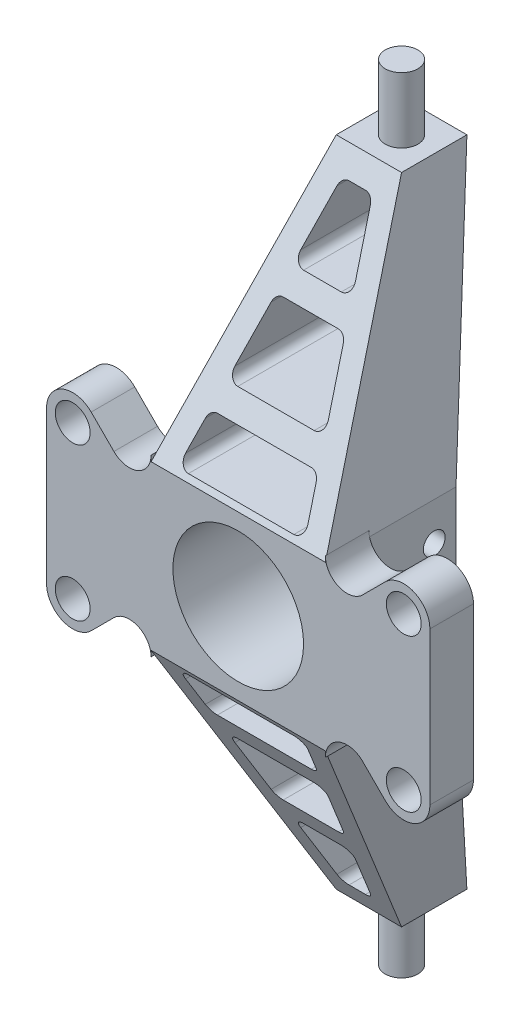
SolidWorks part; units mm, degrees
material "Cast Alloy Steel"
ref_plane "Front Plane" through (0, 0, 0) normal (0, 0, 1) x (1, 0, 0)
ref_plane "Top Plane" through (0, 0, 0) normal (0, 1, 0) x (1, 0, 0)
ref_plane "Right Plane" through (0, 0, 0) normal (1, 0, 0) x (0, 0, -1)
sketch "Sketch1" plane through (0, 0, 0) normal (1, 0, 0) x (0, 0, -1)
  line L1 (-15, -18.75) -> (-15, 18.75)
  line L2 (-15, 18.75) -> (15, 75)
  line L3 (15, 75) -> (30, 75)
  line L4 (30, 75) -> (15, 18.75)
  line L5 (15, 18.75) -> (15, -18.75)
  line L6 (-59.1587, 0) -> (-15, 0) construction
  line L7 (30, -75) -> (15, -18.75)
  line L8 (15, -75) -> (30, -75)
  line L9 (-15, -18.75) -> (15, -75)
  line L10 (15, 0) -> (64.9977, 0) construction
  line L11 (-15, 0) -> (0, 0) construction
  line L12 (0, 0) -> (15, 0) construction
  point P8 (15, 18.8912)
  dimension "D2" = 30
  dimension "D4" = 30
  dimension "D5" = 15
  dimension "D3" = 150
  dimension "D1" = 37.5
extrude "Boss-Extrude1" add sketch "Sketch1" along normal mid plane 40
sketch "Sketch2" plane through (0, 0, 15) normal (0, 0, 1) x (1, 0, 0)
  circle A0 centre (0, 0) radius 15
  dimension "D1" = 30
extrude "Cut-Extrude1" cut sketch "Sketch2" against normal through all both and the other way through all
sketch "Sketch3" plane through (0, 0, 15) normal (0, 0, 1) x (1, 0, 0)
  line L0 (-28.5355, 16.5208) -> (-33.7574, 21.7426)
  line L1 (-20, -18.75) -> (-20, 18.75) construction
  line L2 (-44, 17.5) -> (-44, -17.5)
  line L3 (-33.7574, -21.7426) -> (-28.5355, -16.5208)
  line L4 (-20, -18.75) -> (-20, -20.0563)
  line L5 (-20, 20.0563) -> (-20, 18.75)
  line L6 (-44, 0) -> (13.7226, 0) construction
  arc A0 (-20, -20.0563) -> (-28.5355, -16.5208) centre (-25, -20.0563) ccw
  arc A1 (-20, 20.0563) -> (-28.5355, 16.5208) centre (-25, 20.0563) cw
  arc A2 (-33.7574, -21.7426) -> (-44, -17.5) centre (-38, -17.5) cw
  arc A3 (-44, 17.5) -> (-33.7574, 21.7426) centre (-38, 17.5) cw
  circle A4 centre (-38, 17.5) radius 4
  circle A5 centre (-38, -17.5) radius 4
  arc A6 (-44, -17.5) -> (-33.7574, -21.7426) centre (-38, -17.5) ccw
  circle A7 centre (-38, -17.5) radius 6 construction
  point P8 (-20, -7.9853)
  point P11 (-20, 7.9853)
  point P18 (-44, 0)
  point P24 (0, 0)
  line M8 (-20, 18.75) -> (-20, -18.75)
  dimension "D1" = 5
  dimension "D2" = 2
  dimension "D4" = 8
  dimension "D3" = 35
  dimension "D5" = 18
  dimension "D6" = 45
extrude "Boss-Extrude2" add sketch "Sketch3" against normal blind 10 separate body contours A3 L2 A2 L3 A0 A1 L0 A5 A4 M8
sketch "Sketch5" plane through (0, 75, 0) normal (0, 1, 0) x (1, 0, 0)
  line L0 (0, 22.5) -> (0, 30) construction
  line L1 (20, 30) -> (-20, 30) construction
  line L2 (0, 22.5) -> (20, 22.5) construction
  line L3 (20, 15) -> (20, 30) construction
  circle A0 centre (0, 22.5) radius 3.75
  dimension "D1" = 7.5
extrude "Boss-Extrude3" add sketch "Sketch5" along normal blind 15
mirror "Mirror1" about plane through (0, 0, 0) normal (0, 1, 0) of "Boss-Extrude3"
sketch "Sketch6" plane through (0, 0, 15) normal (0, 0, 1) x (1, 0, 0)
  line L0 (-20, 18.75) -> (-7.5, 75)
  line L1 (20, 75) -> (-20, 75) construction
  line L2 (20, 18.75) -> (7.5, 75)
  line L4 (-20, 18.75) -> (-20, -18.75)
  line L5 (-20, -18.75) -> (20, -18.75)
  line L6 (20, -18.75) -> (20, 18.75)
  line L7 (20, 18.75) -> (-20, 18.75)
  line L10 (20, -18.75) -> (20, 18.75)
  line L12 (-7.5, 75) -> (-20, 75)
  line L16 (-20, 75) -> (-20, 18.75)
  line L17 (-20, 18.75) -> (20, 18.75)
  line L18 (20, 18.75) -> (20, 75)
  line L19 (20, 75) -> (-20, 75)
  line L20 (-20, 75) -> (-20, 18.75)
  line L22 (20, 18.75) -> (20, 75)
  line L23 (20, 75) -> (7.5, 75)
  dimension "D2" = 12.5
  dimension "D1" = 0
  dimension "D3" = 0
extrude "Cut-Extrude2" cut sketch "Sketch6" against normal through all both and the other way through all contours L22 L23 L2 | L20 L0 L12
mirror "Mirror2" about plane through (0, 0, 0) normal (0, 1, 0) of "Cut-Extrude2"
sketch "Sketch7" plane through (0, 0, 0) normal (0, 0, 1) x (1, 0, 0)
  line L0 (-12.107, 20) -> (12.107, 20)
  line L1 (14.0594, 22.4339) -> (12.7261, 28.4339)
  line L2 (1.8848, 70) -> (-1.8848, 70)
  line L3 (-3.8372, 68.4339) -> (-6.2816, 57.4339)
  line L4 (7.5, 75) -> (-7.5, 75) construction
  line L5 (-20, 18.75) -> (-7.5, 75) construction
  line L6 (20, 18.75) -> (7.5, 75) construction
  line L16 (-10.7737, 30) -> (10.7737, 30)
  line L17 (-8.7737, 35) -> (8.7737, 35)
  line L18 (-6.3292, 50) -> (6.3292, 50)
  line L19 (-4.3292, 55) -> (4.3292, 55)
  line L21 (-8.2816, 48.4339) -> (-10.7261, 37.4339)
  line L23 (6.2816, 57.4339) -> (3.8372, 68.4339)
  line L25 (-12.7261, 28.4339) -> (-14.0594, 22.4339)
  line L26 (10.7261, 37.4339) -> (8.2816, 48.4339)
  arc A0 (14.0594, 22.4339) -> (12.107, 20) centre (12.107, 22) cw
  arc A1 (12.7261, 28.4339) -> (10.7737, 30) centre (10.7737, 28) ccw
  arc A2 (-14.0594, 22.4339) -> (-12.107, 20) centre (-12.107, 22) ccw
  arc A3 (-12.7261, 28.4339) -> (-10.7737, 30) centre (-10.7737, 28) cw
  arc A4 (10.7261, 37.4339) -> (8.7737, 35) centre (8.7737, 37) cw
  arc A5 (-8.2816, 48.4339) -> (-6.3292, 50) centre (-6.3292, 48) cw
  arc A6 (8.2816, 48.4339) -> (6.3292, 50) centre (6.3292, 48) ccw
  arc A7 (-8.7737, 35) -> (-10.7261, 37.4339) centre (-8.7737, 37) cw
  arc A8 (6.2816, 57.4339) -> (4.3292, 55) centre (4.3292, 57) cw
  arc A9 (-6.2816, 57.4339) -> (-4.3292, 55) centre (-4.3292, 57) ccw
  arc A10 (3.8372, 68.4339) -> (1.8848, 70) centre (1.8848, 68) ccw
  arc A11 (-1.8848, 70) -> (-3.8372, 68.4339) centre (-1.8848, 68) ccw
  point P16 (0, 50)
  point P27 (-12.378, 30)
  point P30 (11.2669, 35)
  point P33 (-7.9336, 50)
  point P38 (-11.2669, 35)
  point P41 (6.8225, 55)
  dimension "D7" = 2
  dimension "D3" = 5
  dimension "D4" = 5
  dimension "D5" = 10
  dimension "D6" = 15
  dimension "D8" = 5
  dimension "D2" = 15
  dimension "D1" = 5
  dimension "D9" = 5
extrude "Cut-Extrude3" cut sketch "Sketch7" against normal through all both and the other way through all
mirror "Mirror3" about plane through (0, 0, 0) normal (0, 1, 0) of "Cut-Extrude3"
mirror "Mirror6" about plane through (0, 0, 0) normal (1, 0, 0) of "Boss-Extrude2"
combine bodies "Combine1" operation type add bodies to combine 110 103
sketch "Sketch8" plane through (20, 0, 0) normal (1, 0, 0) x (0, 0, -1)
  line L0 (15, 18.75) -> (-5, 18.75) construction
  line L1 (15, 18.75) -> (15, -18.75) construction
  line L2 (10, 10) -> (10, 18.75) construction
  line L3 (10, -10) -> (10, -18.75) construction
  line L4 (15, -18.75) -> (-5, -18.75) construction
  circle A0 centre (10, 10) radius 2.5
  circle A1 centre (10, -10) radius 2.5
  dimension "D3" = 5
  dimension "D1" = 8.75
  dimension "D2" = 5
extrude "Cut-Extrude4" cut sketch "Sketch8" against normal through all
equation "\"A\" = 30"
equation "\"B\" = 150"
equation "\"C\"= 15"
equation "\"D\"= \"B\" / 4"
equation "\"E\"= \"C\" / 2"
equation "\"D2@Sketch1\"=\"A\""
equation "\"D5@Sketch1\"=\"C\""
equation "\"D1@Sketch5\"=\"E\""
equation "\"D1@Boss-Extrude3\"=\"C\""
equation "\"D3@Sketch1\"=\"B\""
equation "\"D1@Sketch1\"=\"D\""
